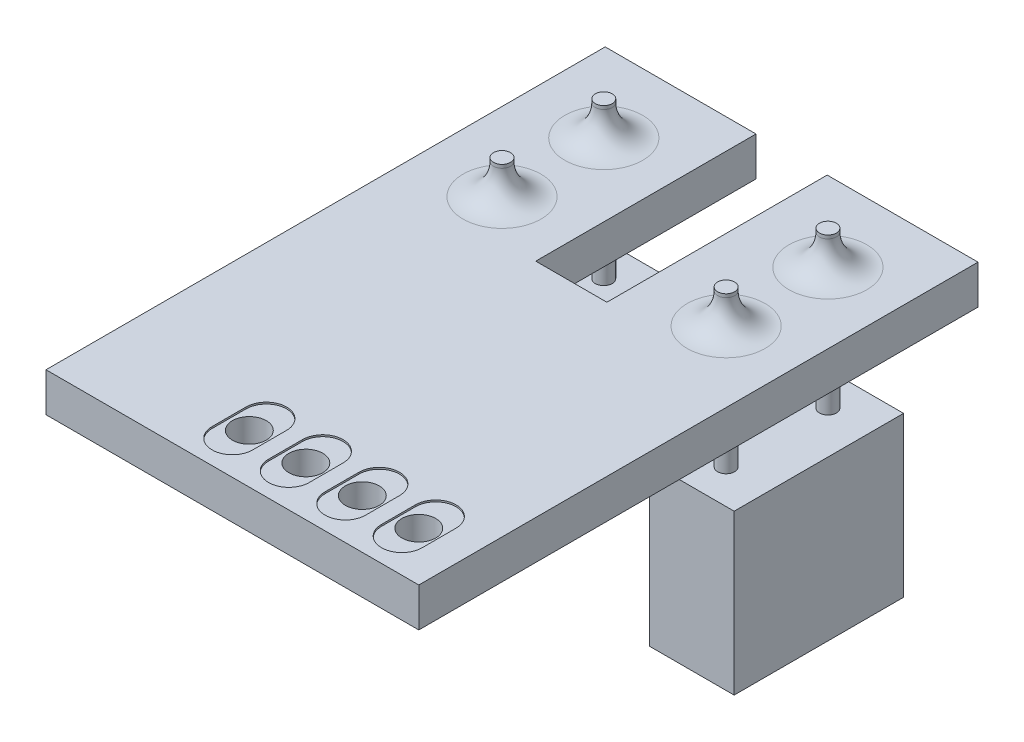
SolidWorks part; units mm, degrees
ref_plane "Front Plane" through (0, 0, 0) normal (0, 0, 1) x (1, 0, 0)
ref_plane "Top Plane" through (0, 0, 0) normal (0, 1, 0) x (1, 0, 0)
ref_plane "Right Plane" through (0, 0, 0) normal (1, 0, 0) x (0, 0, -1)
sketch "Sketch1" plane through (0, 0, 0) normal (0, 1, 0) x (1, 0, 0)
  line L0 (0, 0) -> (0, 16.5)
  line L1 (0, 16.5) -> (4.45, 16.5)
  line L2 (4.45, 16.5) -> (4.45, 10)
  line L3 (4.45, 10) -> (6.55, 10)
  line L4 (6.55, 10) -> (6.55, 16.5)
  line L5 (6.55, 16.5) -> (11, 16.5)
  line L6 (11, 16.5) -> (11, 0)
  line L7 (11, 0) -> (0, 0)
  line L8 (4.5, 1.5) -> (6.1667, 1.5) construction
  line L9 (6.1667, 1.5) -> (7.8333, 1.5) construction
  line L10 (7.8333, 1.5) -> (9.5, 1.5) construction
  circle A0 centre (9.5, 1.5) radius 0.5
  circle A1 centre (7.8333, 1.5) radius 0.5
  circle A2 centre (6.1667, 1.5) radius 0.5
  circle A3 centre (4.5, 1.5) radius 0.5
  dimension "D8" = 1
  dimension "D1" = 11
  dimension "D2" = 16.5
  dimension "D3" = 2.1
  dimension "D4" = 6.5
  dimension "D5" = 1.5
  dimension "D6" = 1.5
  dimension "D7" = 5
extrude "Boss-Extrude1" add sketch "Sketch1" along normal blind 1.15
sketch "Sketch2" plane through (0, 1.15, 0) normal (0, 1, 0) x (1, 0, 0)
  circle A0 centre (2.3033, 14.155) radius 0.25
  circle A1 centre (2.3033, 11.1517) radius 0.25
  circle A2 centre (8.9166, 11.1517) radius 0.25
  circle A3 centre (8.9166, 14.155) radius 0.25
  dimension "D1" = 0.5
extrude "Boss-Extrude2" add sketch "Sketch2" along normal blind 1 and the other way blind 3.6
sketch "Sketch3" plane through (0, -2.45, 0) normal (0, -1, 0) x (1, 0, 0)
  line L1 (1.0533, -10.1379) -> (3.5533, -10.1379)
  line L2 (1.0533, -10.1379) -> (1.0533, -15.1379)
  line L3 (1.0533, -15.1379) -> (3.5533, -15.1379)
  line L4 (3.5533, -10.1379) -> (3.5533, -15.1379)
  line L5 (7.6666, -10.1379) -> (10.1666, -10.1379)
  line L6 (7.6666, -10.1379) -> (7.6666, -15.1379)
  line L7 (7.6666, -15.1379) -> (10.1666, -15.1379)
  line L8 (10.1666, -10.1379) -> (10.1666, -15.1379)
  point P8 (2.3033, -11.1517)
  point P9 (2.3033, -10.1379)
  point P11 (8.9166, -11.1517)
  point P12 (8.9166, -10.1379)
  dimension "D1" = 5
  dimension "D2" = 2.5
extrude "Boss-Extrude3" add sketch "Sketch3" along normal blind 4.7
sketch "Sketch4" plane through (0, 1.15, 0) normal (0, 1, 0) x (1, 0, 0)
  line L0 (4.5, 1) -> (4.5, 2) construction
  line L1 (3.9018, 1) -> (3.9018, 2)
  line L2 (5.0982, 1) -> (5.0982, 2)
  line L3 (6.1667, 1) -> (6.1667, 2) construction
  line L4 (5.5685, 1) -> (5.5685, 2)
  line L5 (6.7649, 1) -> (6.7649, 2)
  line L6 (7.8333, 1) -> (7.8333, 2) construction
  line L7 (7.2351, 1) -> (7.2351, 2)
  line L8 (8.4315, 1) -> (8.4315, 2)
  line L9 (9.5, 1) -> (9.5, 2) construction
  line L10 (8.9018, 1) -> (8.9018, 2)
  line L11 (10.0982, 1) -> (10.0982, 2)
  arc A0 (3.9018, 1) -> (5.0982, 1) centre (4.5, 1) ccw
  arc A1 (5.0982, 2) -> (3.9018, 2) centre (4.5, 2) ccw
  arc A2 (5.5685, 1) -> (6.7649, 1) centre (6.1667, 1) ccw
  arc A3 (6.7649, 2) -> (5.5685, 2) centre (6.1667, 2) ccw
  arc A4 (7.2351, 1) -> (8.4315, 1) centre (7.8333, 1) ccw
  arc A5 (8.4315, 2) -> (7.2351, 2) centre (7.8333, 2) ccw
  arc A6 (8.9018, 1) -> (10.0982, 1) centre (9.5, 1) ccw
  arc A7 (10.0982, 2) -> (8.9018, 2) centre (9.5, 2) ccw
  circle A8 centre (4.5, 1.5) radius 0.5 construction
  point P2 (4.5, 1.5)
  point P9 (6.1667, 1.5)
  point P17 (7.8333, 1.5)
  point P25 (9.5, 1.5)
extrude "Cut-Extrude1" cut sketch "Sketch4" against normal blind 0.05
fillet "Fillet1" radius 0.9 4 edges at (8.9166, 1.15, -14.405) (8.9166, 1.15, -11.4017) (2.3033, 1.15, -14.405) (2.3033, 1.15, -11.4017)
